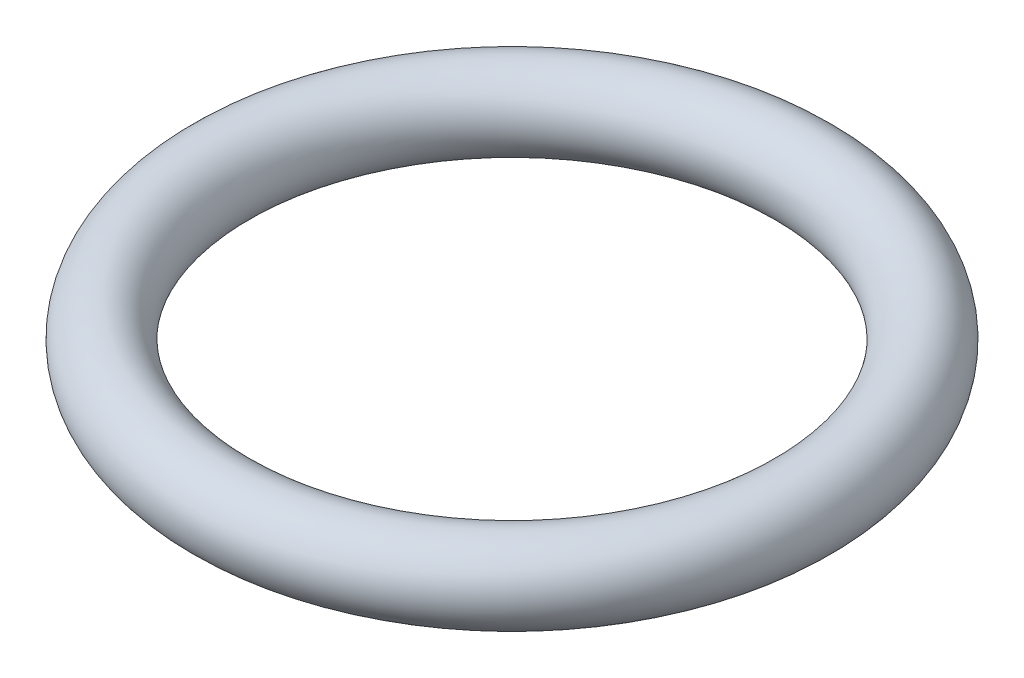
SolidWorks part; units mm, degrees
material "Stainless Steel 304"
ref_plane "Front Plane" through (0, 0, 0) normal (0, 0, 1) x (1, 0, 0)
ref_plane "Top Plane" through (0, 0, 0) normal (0, 1, 0) x (1, 0, 0)
ref_plane "Right Plane" through (0, 0, 0) normal (1, 0, 0) x (0, 0, -1)
sketch "Sketch1" plane through (0, 0, 0) normal (0, 0, 1) x (1, 0, 0)
  line L0 (0, 0) -> (0, 26.7652) construction
  line L1 (0, 0) -> (29.3687, 0) construction
  circle A0 centre (29.3687, 0) radius 3.9687
  point P5 (25.4, 0)
  dimension "D1" = 7.9375
  dimension "D2" = 50.8
revolve "Revolve1" add sketch "Sketch1" angle 360 about L0
